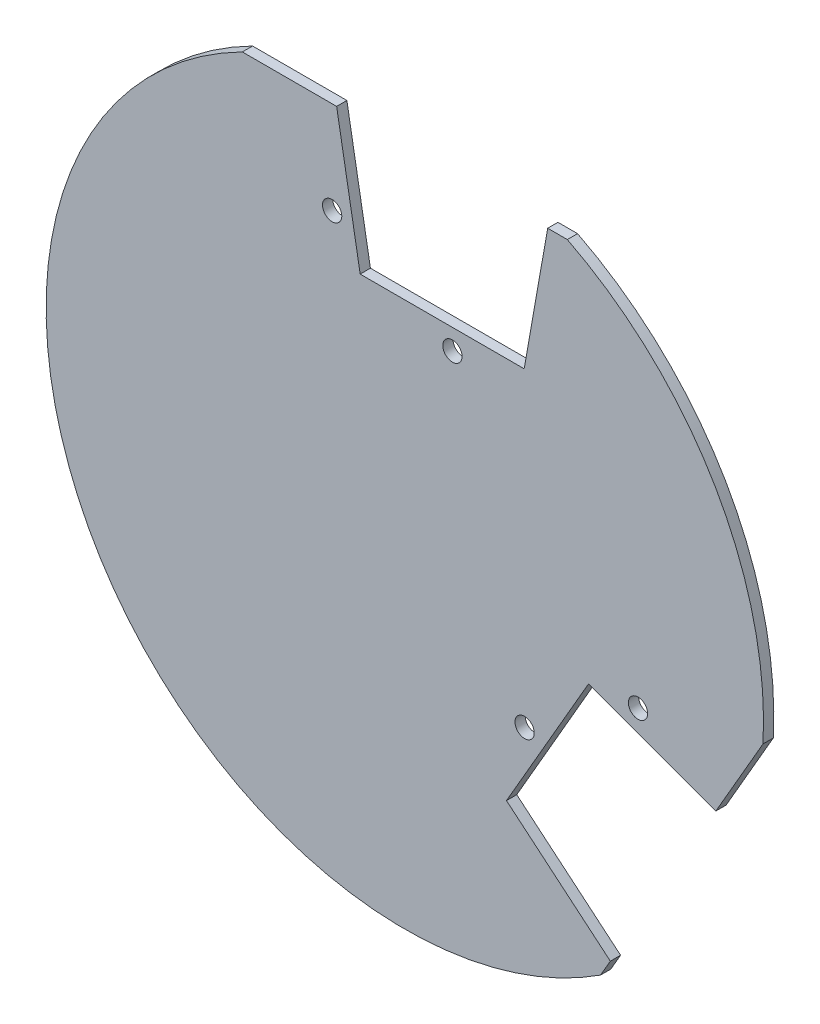
SolidWorks part; units mm, degrees
material "Balsa"
ref_plane "Plan de face" through (0, 0, 0) normal (0, 0, 1) x (1, 0, 0)
ref_plane "Plan de dessus" through (0, 0, 0) normal (0, 1, 0) x (1, 0, 0)
ref_plane "Plan de droite" through (0, 0, 0) normal (1, 0, 0) x (0, 0, -1)
sketch "Esquisse1" plane through (0, 0, 0) normal (0, 0, 1) x (1, 0, 0)
  circle A0 centre (0, 0) radius 175
extrude "Boss.-Extru.1" add sketch "Esquisse1" along normal blind 5
sketch "Esquisse2" plane through (0, 0, 0) normal (0, 0, -1) x (-1, 0, 0)
  line L1 (-18.2204, 90.8876) -> (-18.2204, 0) construction
  line L3 (0, 0) -> (-290.6498, 0) construction
  line L5 (21.7796, 90.8876) -> (33.2633, 156.0152)
  line L6 (33.2633, 156.0152) -> (79.2734, 156.0152)
  line L7 (79.2734, 156.0152) -> (79.2734, 185.2461)
  line L8 (-58.2204, 90.8876) -> (-69.7042, 156.0152)
  line L9 (-69.7042, 156.0152) -> (-115.7142, 156.0152)
  line L10 (-115.7142, 156.0152) -> (-115.7142, 185.2461)
  line L11 (-115.7142, 185.2461) -> (79.2734, 185.2461)
  line L12 (21.7796, 90.8876) -> (-58.2204, 90.8876)
  line L13 (-89.6008, -26.5821) -> (-151.7448, -49.2007)
  line L14 (-151.7448, -49.2007) -> (-174.7498, -9.3548)
  line L15 (-174.7498, -9.3548) -> (-200.0645, -23.9703)
  line L16 (-49.6008, -95.8642) -> (-100.261, -138.3732)
  line L17 (-100.261, -138.3732) -> (-77.256, -178.2191)
  line L18 (-77.256, -178.2191) -> (-102.5707, -192.8345)
  line L19 (-102.5707, -192.8345) -> (-200.0645, -23.9703)
  line L20 (-89.6008, -26.5821) -> (-49.6008, -95.8642)
  line L21 (-69.6008, -61.2232) -> (9.1102, -15.7794) construction
  line L22 (0, 0) -> (87.5, -151.5544) construction
  circle A0 centre (-23.2204, 80.8876) radius 4.7
  circle A1 centre (35.4604, 110.8876) radius 4.7
  circle A2 centre (-58.4405, -60.5533) radius 4.7
  circle A3 centre (-113.7617, -24.7342) radius 4.7
  circle A4 centre (0, 0) radius 175 construction
  point P43 (0, 0)
  dimension "D5" = 9.4
  dimension "D6" = 9.4
  dimension "D1" = 2
  dimension "D2" = 90.8876
  dimension "D3" = 18.2204
  dimension "D4" = 100
  dimension "D7" = 80
  dimension "D8" = 65.1275
extrude "Enlèv. mat.-Extru.1" cut sketch "Esquisse2" against normal blind 5
